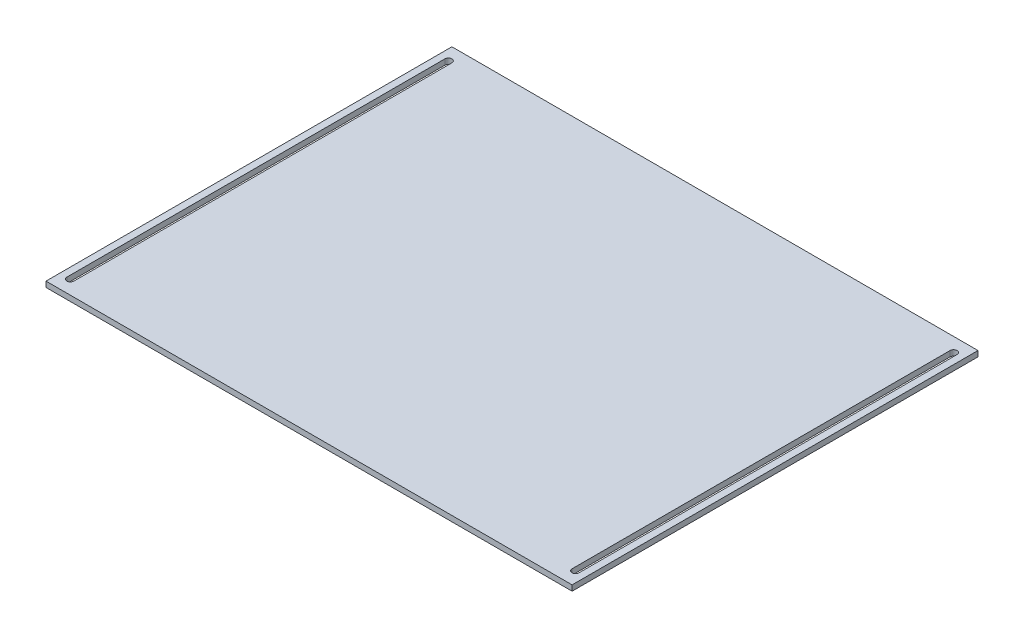
SolidWorks part; units mm, degrees
ref_plane "Front Plane" through (0, 0, 0) normal (0, 0, 1) x (1, 0, 0)
ref_plane "Top Plane" through (0, 0, 0) normal (0, 1, 0) x (1, 0, 0)
ref_plane "Right Plane" through (0, 0, 0) normal (1, 0, 0) x (0, 0, -1)
sketch "Sketch1" plane through (0, 0, 0) normal (0, 1, 0) x (1, 0, 0)
  line L1 (0, 0) -> (-302, 0)
  line L2 (0, 0) -> (0, 233)
  line L3 (0, 233) -> (-302, 233)
  line L4 (-302, 0) -> (-302, 233)
  dimension "D1" = 302
  dimension "D2" = 233
extrude "Boss-Extrude1" add sketch "Sketch1" along normal blind 3.175
sketch "Sketch2" plane through (0, 3.175, 0) normal (0, 1, 0) x (1, 0, 0)
  line L0 (-302, 219.8935) -> (-296, 219.8935) construction
  line L1 (-302, 233) -> (-302, 0) construction
  line L2 (-296, 233) -> (-296, 0) construction
  line L3 (0, 233) -> (-302, 233) construction
  line L4 (-302, 0) -> (0, 0) construction
  line L5 (-296, 0) -> (-296, 8) construction
  line L6 (-296, 233) -> (-296, 225) construction
  line L7 (-296, 225) -> (-296, 8) construction
  line L8 (-294, 225) -> (-294, 8)
  line L9 (-298, 225) -> (-298, 8)
  line L10 (0, 219.8935) -> (-6, 219.8935) construction
  line L11 (0, 0) -> (0, 233) construction
  line L12 (-6, 233) -> (-6, 0) construction
  line L13 (-6, 233) -> (-6, 225) construction
  line L14 (-6, 0) -> (-6, 8) construction
  line L15 (-6, 225) -> (-6, 8) construction
  line L16 (-4, 225) -> (-4, 8)
  line L17 (-8, 225) -> (-8, 8)
  arc A0 (-294, 225) -> (-298, 225) centre (-296, 225) ccw
  arc A1 (-298, 8) -> (-294, 8) centre (-296, 8) ccw
  arc A2 (-4, 225) -> (-8, 225) centre (-6, 225) ccw
  arc A3 (-8, 8) -> (-4, 8) centre (-6, 8) ccw
  point P14 (-296, 116.5)
  point P27 (-6, 116.5)
  dimension "D4" = 2
  dimension "D6" = 2
  dimension "D1" = 6
  dimension "D2" = 8
  dimension "D3" = 6
  dimension "D5" = 8
extrude "Cut-Extrude1" cut sketch "Sketch2" against normal through all
